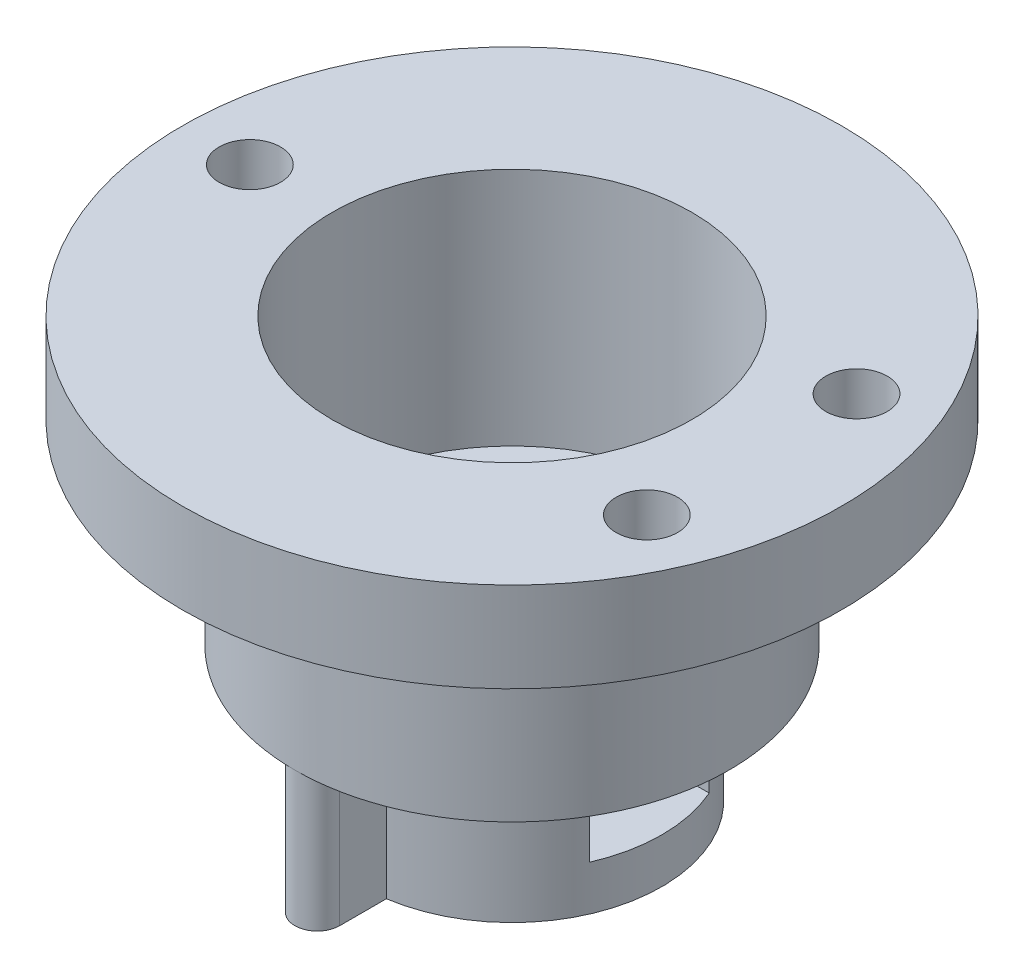
SolidWorks part; units mm, degrees
ref_plane "Alzado" through (0, 0, 0) normal (0, 0, 1) x (1, 0, 0)
ref_plane "Planta" through (0, 0, 0) normal (0, 1, 0) x (1, 0, 0)
ref_plane "Vista lateral" through (0, 0, 0) normal (1, 0, 0) x (0, 0, -1)
sketch "Croquis5" plane through (0, 0, 0) normal (0, 1, 0) x (1, 0, 0)
  circle A0 centre (0, 0) radius 10
  dimension "D1" = 20
extrude "Saliente-Extruir1" add sketch "Croquis5" along normal blind 9
sketch "Croquis6" plane through (0, 9, 0) normal (0, 1, 0) x (1, 0, 0)
  circle A0 centre (0, 0) radius 14.5
  dimension "D1" = 29
extrude "Saliente-Extruir2" add sketch "Croquis6" along normal blind 13
sketch "Croquis7" plane through (0, 22, 0) normal (0, 1, 0) x (1, 0, 0)
  circle A0 centre (0, 0) radius 22
  dimension "D1" = 44
extrude "Saliente-Extruir3" add sketch "Croquis7" along normal blind 6
sketch "Croquis8" plane through (0, 28, 0) normal (0, 1, 0) x (1, 0, 0)
  circle A0 centre (0, 0) radius 12
  dimension "D1" = 24
extrude "Cortar-Extruir1" cut sketch "Croquis8" against normal blind 16
sketch "Croquis9" plane through (0, 12, 0) normal (0, 1, 0) x (1, 0, 0)
  circle A0 centre (0, 0) radius 3
  dimension "D1" = 6
extrude "Cortar-Extruir2" cut sketch "Croquis9" against normal blind 16
sketch "Croquis10" plane through (0, 0, 0) normal (0, 0, 1) x (1, 0, 0)
  line L0 (-1.5, 0) -> (1.5, 0)
  line L1 (1.5, 0) -> (1.5, 9)
  line L2 (1.5, 9) -> (-1.5, 9)
  line L3 (-1.5, 9) -> (-1.5, 0)
  line L4 (-10, 9) -> (10, 9) construction
  point P4 (0, 0)
  dimension "D1" = 3
extrude "Saliente-Extruir4" add sketch "Croquis10" along normal blind 13
sketch "Croquis11" plane through (0, 0, 0) normal (0, -1, 0) x (1, 0, 0)
  line L0 (1.5, 13) -> (-1.5, 13) construction
  line L1 (-1.5, 13) -> (1.5, 13)
  arc A0 (1.5, 13) -> (-1.5, 13) centre (0, 13) ccw
extrude "Saliente-Extruir5" add sketch "Croquis11" against normal blind 13
sketch "Croquis12" plane through (0, 0, 0) normal (1, 0, 0) x (0, 0, -1)
  line L0 (0, 0) -> (0, 3) construction
  line L1 (-4, 3) -> (4, 3)
  line L2 (-4, 3) -> (-4, 6.8)
  line L3 (-4, 6.8) -> (4, 6.8)
  line L4 (4, 6.8) -> (4, 3)
  point P6 (0, 3)
  dimension "D1" = 3
  dimension "D2" = 8
  dimension "D3" = 3.8
extrude "Cortar-Extruir3" cut sketch "Croquis12" along normal blind 13 contours L4 L1 L2 L3
sketch "Croquis13" plane through (0, 12, 0) normal (0, 1, 0) x (1, 0, 0)
  circle A0 centre (0, 0) radius 3
extrude "Cortar-Extruir4" cut sketch "Croquis13" against normal blind 13
sketch "Croquis14" plane through (0, 28, 0) normal (0, 1, 0) x (1, 0, 0)
  line L0 (-22, 0) -> (-17.5, 0) construction
  line L1 (15.9997, 7) -> (15.9997, -7) construction
  line L2 (0, 0) -> (15.9997, 7) construction
  line L3 (0, 0) -> (15.9997, -7) construction
  circle A1 centre (-17.5, 0) radius 2.05
  circle A2 centre (0, 0) radius 22 construction
  circle A3 centre (15.9997, 7) radius 2.05
  circle A4 centre (15.9997, -7) radius 2.05
  dimension "D2" = 4.1
  dimension "D4" = 17.464
  dimension "D1" = 4.5
  dimension "D3" = 14
  dimension "D5" = 17.464
extrude "Cortar-Extruir5" cut sketch "Croquis14" against normal blind 13
